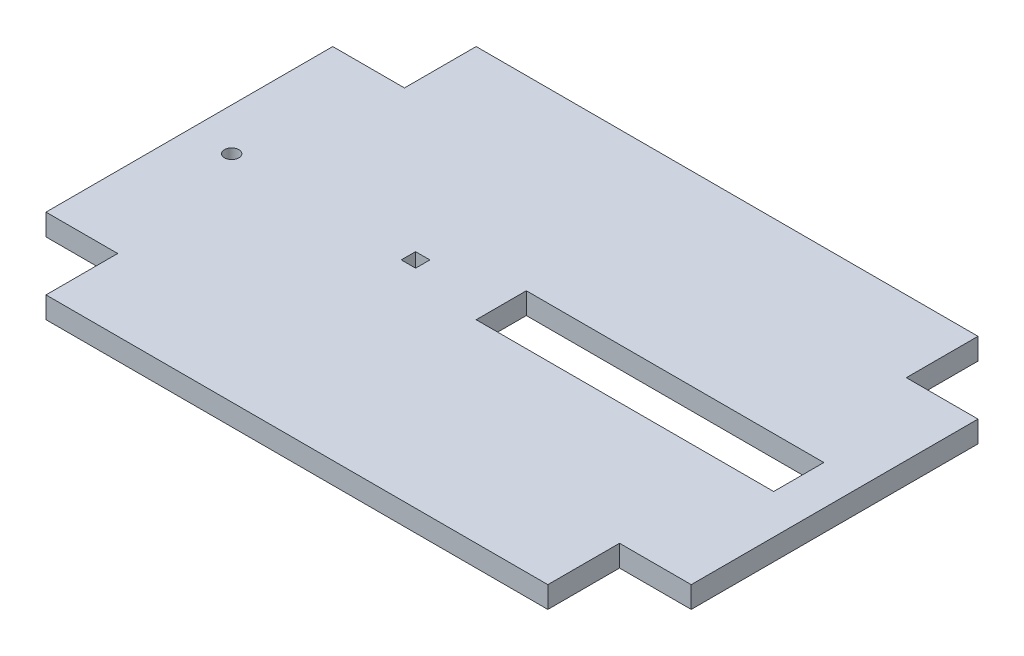
SolidWorks part; units mm, degrees
ref_plane "Front Plane" through (0, 0, 0) normal (0, 0, 1) x (1, 0, 0)
ref_plane "Top Plane" through (0, 0, 0) normal (0, 1, 0) x (1, 0, 0)
ref_plane "Right Plane" through (0, 0, 0) normal (1, 0, 0) x (0, 0, -1)
sketch "Sketch1" plane through (0, 0, 0) normal (0, 1, 0) x (1, 0, 0)
  line L0 (-401.7852, 228.8036) -> (-401.7852, -371.1964)
  line L1 (-401.7852, 228.8036) -> (498.2148, 228.8036)
  line L5 (-401.7852, -371.1964) -> (498.2148, -371.1964)
  line L6 (498.2148, -371.1964) -> (498.2148, 228.8036)
  dimension "D1" = 900
  dimension "D2" = 600
extrude "Boss-Extrude1" add sketch "Sketch1" along normal blind 30
sketch "Sketch2" plane through (0, 30, 0) normal (0, 1, 0) x (1, 0, 0)
  line L0 (-401.7852, 228.8036) -> (-401.7852, 128.8036)
  line L1 (-401.7852, 228.8036) -> (-401.7852, -371.1964) construction
  line L2 (-401.7852, 128.8036) -> (-301.7852, 128.8036)
  line L3 (-301.7852, 128.8036) -> (-301.7852, 228.8036)
  line L4 (498.2148, 228.8036) -> (-401.7852, 228.8036) construction
  line L5 (-301.7852, 228.8036) -> (-401.7852, 228.8036)
  line L24 (-401.7852, -371.1964) -> (-301.7852, -371.1964)
  line L25 (-401.7852, -371.1964) -> (498.2148, -371.1964) construction
  line L26 (-301.7852, -371.1964) -> (-301.7852, -271.1964)
  line L27 (-301.7852, -271.1964) -> (-401.7852, -271.1964)
  line L28 (-401.7852, 228.8036) -> (-401.7852, -371.1964) construction
  line L29 (-401.7852, -271.1964) -> (-401.7852, -371.1964)
  line L30 (498.2148, -371.1964) -> (498.2148, -271.1964)
  line L31 (498.2148, -371.1964) -> (498.2148, 228.8036) construction
  line L32 (498.2148, -271.1964) -> (398.2148, -271.1964)
  line L33 (398.2148, -271.1964) -> (398.2148, -371.1964)
  line L34 (398.2148, -371.1964) -> (498.2148, -371.1964)
  line L36 (498.2148, 228.8036) -> (498.2148, 128.8036)
  line L37 (498.2148, 128.8036) -> (398.2148, 128.8036)
  line L38 (398.2148, 128.8036) -> (398.2148, 228.8036)
  line L39 (498.2148, 228.8036) -> (-401.7852, 228.8036) construction
  line L40 (398.2148, 228.8036) -> (498.2148, 228.8036)
  point P32 (448.2148, -271.1964)
  dimension "D1" = 100
  dimension "D2" = 100
  dimension "100" = 100
  dimension "D3" = 100
  dimension "D4" = 100
  dimension "D5" = 100
  dimension "D6" = 100
  dimension "D7" = 100
  dimension "D8" = 100
extrude "Cut-Extrude1" cut sketch "Sketch2" against normal through all
sketch "Sketch4" plane through (0, 30, 0) normal (0, 1, 0) x (1, 0, 0)
  line L1 (-96.2852, -81.1964) -> (-76.2852, -81.1964)
  line L2 (-96.2852, -81.1964) -> (-96.2852, -61.1964)
  line L3 (-96.2852, -61.1964) -> (-76.2852, -61.1964)
  line L4 (-76.2852, -81.1964) -> (-76.2852, -61.1964)
  line L5 (-96.2852, -81.1964) -> (-76.2852, -61.1964) construction
  line L6 (-96.2852, -61.1964) -> (-76.2852, -81.1964) construction
  circle A1 centre (-342.7852, -71.1964) radius 10
  dimension "D1" = 20
extrude "Cut-Extrude2" cut sketch "Sketch4" against normal blind 176
sketch "Sketch5" plane through (0, 30, 0) normal (0, 1, 0) x (1, 0, 0)
  line L1 (443.2148, -31.1964) -> (443.2148, -101.1964)
  line L3 (28.2148, -31.1964) -> (28.2148, -101.1964)
  line L4 (28.2148, -101.1964) -> (443.2148, -101.1964)
  line L7 (443.2148, -31.1964) -> (28.2148, -31.1964)
  dimension "D2" = 70
extrude "Cut-Extrude3" cut sketch "Sketch5" against normal blind 110
